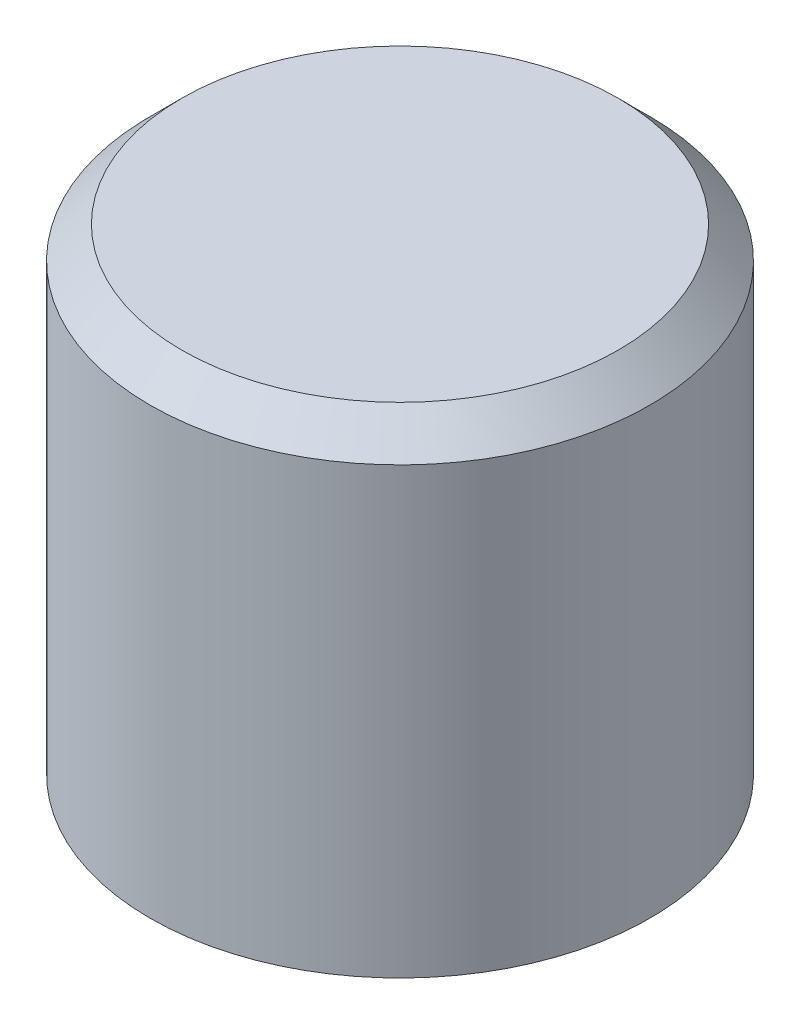
SolidWorks part; units mm, degrees
ref_plane "Спереди" through (0, 0, 0) normal (0, 0, 1) x (1, 0, 0)
ref_plane "Сверху" through (0, 0, 0) normal (0, 1, 0) x (1, 0, 0)
ref_plane "Справа" through (0, 0, 0) normal (1, 0, 0) x (0, 0, -1)
sketch "Эскиз1" plane through (0, 0, 0) normal (0, 1, 0) x (1, 0, 0)
  circle A0 centre (0, 0) radius 7.875
  dimension "D1" = 15.75
extrude "Бобышка-Вытянуть1" add sketch "Эскиз1" along normal blind 15
chamfer "Фаска1" distance 1 angle 45 1 edges at (0, 15, 7.875)
